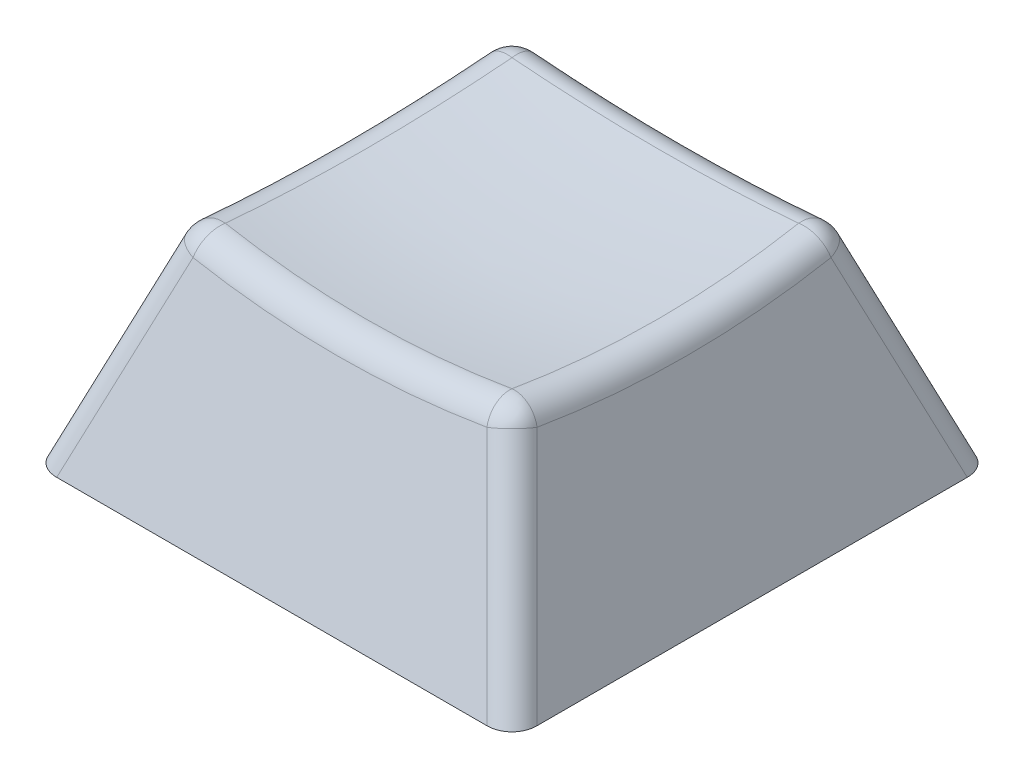
SolidWorks part; units mm, degrees
ref_plane "Front Plane" through (0, 0, 0) normal (0, 0, 1) x (1, 0, 0)
ref_plane "Top Plane" through (0, 0, 0) normal (0, 1, 0) x (1, 0, 0)
ref_plane "Right Plane" through (0, 0, 0) normal (1, 0, 0) x (0, 0, -1)
sketch "Sketch1" plane through (0, 0, 0) normal (0, 1, 0) x (1, 0, 0)
  line L1 (9, 9) -> (-9, 9)
  line L2 (9, 9) -> (9, -9)
  line L3 (9, -9) -> (-9, -9)
  line L4 (-9, 9) -> (-9, -9)
  line L5 (9, 9) -> (-9, -9) construction
  line L6 (9, -9) -> (-9, 9) construction
  point P0 (0, 0)
  dimension "D1" = 18
extrude "Boss-Extrude1" add sketch "Sketch1" along normal blind 8 draft 19.7 contours L2 L1 L4 L3
ref_plane "Plane1" through (0, 0, 0) normal (0.7071, 0, -0.7071) x (-0.7071, 0, -0.7071)
sketch "Sketch3" plane through (0, 0, 0) normal (0.7071, 0, -0.7071) x (-0.7071, 0, -0.7071)
  line L0 (0, 0) -> (0, 47.0475) construction
  line L1 (40, 47.0475) -> (-40, 47.0475) construction
  line L2 (-40, 47.0475) -> (40, 47.0475)
  arc A0 (-40, 47.0475) -> (40, 47.0475) centre (0, 47.0475) ccw
  point P6 (0, 47.0475)
  dimension "D1" = 40
revolve "Cut-Revolve2" cut sketch "Sketch3" angle 360 about L2
fillet "Fillet1" radius 1 8 edges at (0, 7.5464, -6.298) (6.298, 7.5464, 0) (0, 7.5464, 6.298) (-6.298, 7.5464, 0) (-7.5678, 4, -7.5678) (7.5678, 4, 7.5678) (7.5678, 4, -7.5678) (-7.5678, 4, 7.5678)
shell "Shell1" thickness 1.5
sketch "Sketch4" plane through (0, 0, 0) normal (0, -1, 0) x (1, 0, 0)
  circle A0 centre (0, 0) radius 2.75
  circle A1 centre (0, 0) radius 2
  dimension "D1" = 5.5
  dimension "D2" = 4
extrude "Boss-Extrude2" add sketch "Sketch4" against normal up to next contours A1 | A0 A1
sketch "Sketch6" plane through (0, 0, 0) normal (0, -1, 0) x (1, 0, 0)
  line L0 (-2.75, 0) -> (2.75, 0) construction
  line L1 (0, -2.75) -> (0, 2.75) construction
  line L2 (0, -2.05) -> (-0.55, -2.05)
  line L3 (-0.55, -2.05) -> (-0.55, -0.55)
  line L4 (-0.55, -0.55) -> (-2.05, -0.55)
  line L5 (-2.05, -0.55) -> (-2.05, 0)
  line L6 (-2.05, 0) -> (-2.05, 0.55)
  line L7 (-2.05, 0.55) -> (-0.55, 0.55)
  line L8 (-0.55, 0.55) -> (-0.55, 2.05)
  line L9 (-0.55, 2.05) -> (0, 2.05)
  line L10 (0, -2.05) -> (0.55, -2.05)
  line L11 (0.55, -2.05) -> (0.55, -0.55)
  line L12 (0.55, -0.55) -> (2.05, -0.55)
  line L13 (2.05, -0.55) -> (2.05, 0)
  line L14 (2.05, 0) -> (2.05, 0.55)
  line L15 (2.05, 0.55) -> (0.55, 0.55)
  line L16 (0.55, 0.55) -> (0.55, 2.05)
  line L17 (0.55, 2.05) -> (0, 2.05)
  circle A0 centre (0, 0) radius 2.75 construction
  circle A1 centre (0, 0) radius 2.75 construction
  dimension "D1" = 0.55
  dimension "D2" = 2.05
extrude "Cut-Extrude2" cut sketch "Sketch6" against normal up to surface (5.5548 mm away)
ref_plane "Plane2" through (0, 4.7625, 0) normal (0, -1, 0) x (-1, 0, 0)
sketch "Sketch8" plane through (0, 4.7625, 0) normal (0, -1, 0) x (-1, 0, 0)
  line L0 (-5.1865, 5.1865) -> (-7.4067, 7.4067) construction
  line L1 (6.2966, -6.2966) -> (-6.2966, -6.2966)
  line L2 (6.2966, -6.2966) -> (6.2966, 6.2966)
  line L3 (6.2966, 6.2966) -> (-6.2966, 6.2966)
  line L4 (-6.2966, -6.2966) -> (-6.2966, 6.2966)
  line L5 (6.2966, -6.2966) -> (-6.2966, 6.2966) construction
  line L6 (6.2966, 6.2966) -> (-6.2966, -6.2966) construction
  line L7 (-5.1865, -5.1865) -> (-7.4067, -7.4067) construction
  point P0 (0, 0)
extrude "Boss-Extrude3" add sketch "Sketch8" against normal up to surface (1.7516 mm away)
